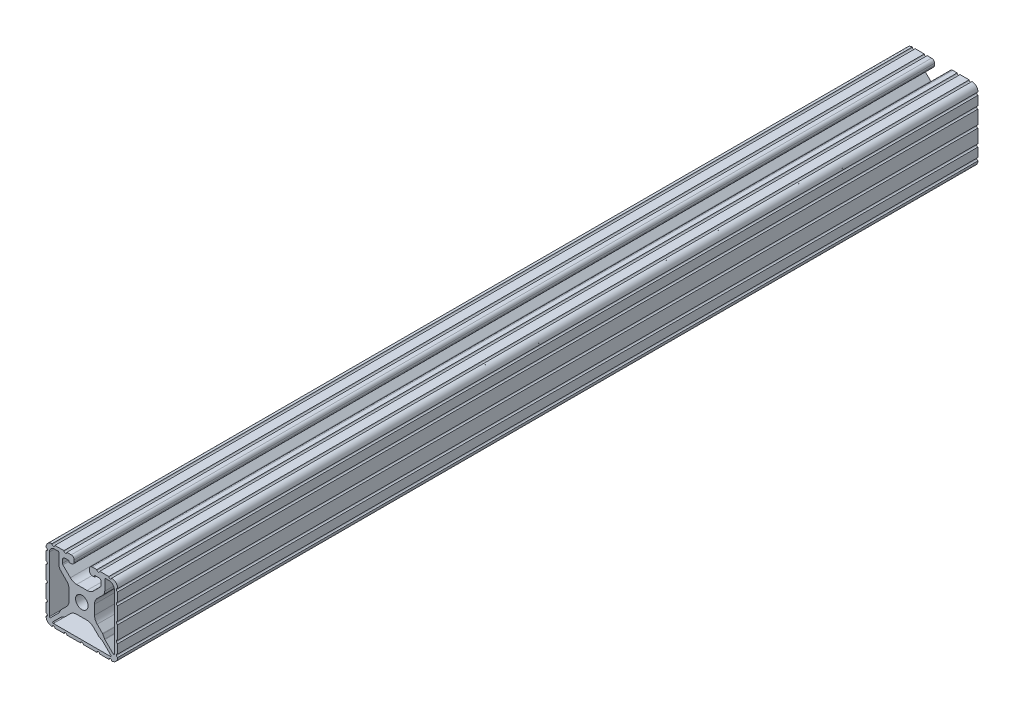
SolidWorks part; units mm, degrees
material "6105-T5 Aluminum"
ref_plane "Front Plane" through (0, 0, 0) normal (0, 0, 1) x (1, 0, 0)
ref_plane "Top Plane" through (0, 0, 0) normal (0, 1, 0) x (1, 0, 0)
ref_plane "Right Plane" through (0, 0, 0) normal (1, 0, 0) x (0, 0, -1)
sketch "Sketch1" plane through (0, 0, 0) normal (0, 0, 1) x (1, 0, 0)
  line L0 (17.272, -15.1936) -> (17.272, 14.478)
  line L1 (12.2663, -11.0145) -> (16.6875, -15.4357)
  line L2 (11.1044, -8.9951) -> (12.14, -10.8475)
  line L3 (8.1475, -5.9974) -> (10.9781, -8.8281)
  line L4 (6.7564, 2.525) -> (6.7564, -2.6388)
  line L5 (11.2435, 8.979) -> (8.1479, 5.8839)
  line L6 (12.1736, 16.891) -> (12.1736, 11.2243)
  line L7 (14.478, 17.272) -> (12.5546, 17.272)
  line L8 (-12.1736, 11.2243) -> (-12.1736, 16.891)
  line L9 (-8.1479, 5.8839) -> (-11.2435, 8.979)
  line L10 (-6.7564, -2.6388) -> (-6.7564, 2.525)
  line L11 (-10.9781, -8.8281) -> (-8.1475, -5.9974)
  line L12 (-12.14, -10.8475) -> (-11.1044, -8.9951)
  line L13 (-16.6875, -15.4357) -> (-12.2663, -11.0145)
  line L14 (-17.272, 14.478) -> (-17.272, -15.1936)
  line L15 (-12.5546, 17.272) -> (-14.478, 17.272)
  line L16 (15.3589, -16.6216) -> (11.091, -12.3537)
  line L17 (-15.0895, -17.272) -> (15.0895, -17.272)
  line L18 (-11.091, -12.3537) -> (-15.3589, -16.6216)
  line L19 (-9.0722, -11.1921) -> (-10.924, -12.2274)
  line L20 (-6.1016, -8.262) -> (-8.9052, -11.0658)
  line L21 (2.7429, -6.8707) -> (-2.7429, -6.8707)
  line L22 (8.9052, -11.0658) -> (6.1016, -8.262)
  line L23 (10.924, -12.2274) -> (9.0722, -11.1921)
  line L24 (6.8141, 15.8247) -> (9.017, 15.8247)
  line L25 (10.287, 14.5547) -> (10.287, 12.8154)
  line L26 (10.0266, 12.1868) -> (6.1008, 8.2616)
  line L27 (2.7424, 6.8707) -> (-2.7424, 6.8707)
  line L28 (-6.1008, 8.2616) -> (-10.0266, 12.1868)
  line L29 (-10.287, 12.8154) -> (-10.287, 14.5547)
  line L30 (-9.017, 15.8247) -> (-6.8141, 15.8247)
  line L31 (-6.8141, 15.8247) -> (-6.8141, 14.986)
  line L32 (-6.8141, 14.986) -> (-5.6388, 14.986)
  line L33 (-4.064, 16.5608) -> (-4.064, 17.4752)
  line L34 (-5.6388, 19.05) -> (-7.9756, 19.05)
  line L35 (-9.4996, 19.05) -> (-14.3256, 19.05)
  line L36 (-15.8496, 19.05) -> (-15.875, 19.05)
  line L37 (-19.05, 15.875) -> (-19.05, 15.8496)
  line L38 (-19.05, 14.3256) -> (-19.05, 9.4996)
  line L39 (-19.05, 7.9756) -> (-19.05, 0.762)
  line L40 (-19.05, -0.762) -> (-19.05, -7.9756)
  line L41 (-19.05, -9.4996) -> (-19.05, -14.3256)
  line L42 (-19.05, -15.8496) -> (-19.05, -15.875)
  line L43 (-15.875, -19.05) -> (-15.8496, -19.05)
  line L44 (-14.3256, -19.05) -> (-9.4996, -19.05)
  line L45 (-7.9756, -19.05) -> (-0.762, -19.05)
  line L46 (0.762, -19.05) -> (7.9756, -19.05)
  line L47 (9.4996, -19.05) -> (14.3256, -19.05)
  line L48 (15.8496, -19.05) -> (15.875, -19.05)
  line L49 (19.05, -15.875) -> (19.05, -15.8496)
  line L50 (19.05, -14.3256) -> (19.05, -9.4996)
  line L51 (19.05, -7.9756) -> (19.05, -0.762)
  line L52 (19.05, 0.762) -> (19.05, 7.9756)
  line L53 (19.05, 9.4996) -> (19.05, 14.3256)
  line L54 (19.05, 15.8496) -> (19.05, 15.875)
  line L55 (15.875, 19.05) -> (15.8496, 19.05)
  line L56 (14.3256, 19.05) -> (9.4996, 19.05)
  line L57 (7.9756, 19.05) -> (5.6388, 19.05)
  line L58 (4.064, 17.4752) -> (4.064, 16.5608)
  line L59 (5.6388, 14.986) -> (6.8141, 14.986)
  line L60 (6.8141, 14.986) -> (6.8141, 15.8247)
  circle A0 centre (0, 0) radius 3.3274
  arc A1 (17.272, 14.478) -> (14.478, 17.272) centre (14.478, 14.478) ccw
  arc A2 (16.6875, -15.4357) -> (17.272, -15.1936) centre (16.9296, -15.1936) ccw
  arc A3 (12.14, -10.8475) -> (12.2663, -11.0145) centre (12.8051, -10.4757) ccw
  arc A4 (11.1044, -8.9951) -> (10.9781, -8.8281) centre (10.4393, -9.3669) ccw
  arc A5 (6.7564, -2.6388) -> (8.1475, -5.9974) centre (11.5062, -2.6388) ccw
  arc A6 (8.1479, 5.8839) -> (6.7564, 2.525) centre (11.5062, 2.525) ccw
  arc A7 (11.2435, 8.979) -> (12.1736, 11.2243) centre (8.9986, 11.2243) ccw
  arc A8 (12.5546, 17.272) -> (12.1736, 16.891) centre (12.5546, 16.891) ccw
  arc A9 (-12.1736, 16.891) -> (-12.5546, 17.272) centre (-12.5546, 16.891) ccw
  arc A10 (-12.1736, 11.2243) -> (-11.2435, 8.979) centre (-8.9986, 11.2243) ccw
  arc A11 (-6.7564, 2.525) -> (-8.1479, 5.8839) centre (-11.5062, 2.525) ccw
  arc A12 (-8.1475, -5.9974) -> (-6.7564, -2.6388) centre (-11.5062, -2.6388) ccw
  arc A13 (-10.9781, -8.8281) -> (-11.1044, -8.9951) centre (-10.4393, -9.3669) ccw
  arc A14 (-12.2663, -11.0145) -> (-12.14, -10.8475) centre (-12.8051, -10.4757) ccw
  arc A15 (-17.272, -15.1936) -> (-16.6875, -15.4357) centre (-16.9296, -15.1936) ccw
  arc A16 (-14.478, 17.272) -> (-17.272, 14.478) centre (-14.478, 14.478) ccw
  arc A17 (11.091, -12.3537) -> (10.924, -12.2274) centre (10.5522, -12.8925) ccw
  arc A18 (15.0895, -17.272) -> (15.3589, -16.6216) centre (15.0895, -16.891) ccw
  arc A19 (-15.3589, -16.6216) -> (-15.0895, -17.272) centre (-15.0895, -16.891) ccw
  arc A20 (-10.924, -12.2274) -> (-11.091, -12.3537) centre (-10.5522, -12.8925) ccw
  arc A21 (-9.0722, -11.1921) -> (-8.9052, -11.0658) centre (-9.4441, -10.527) ccw
  arc A22 (-2.7429, -6.8707) -> (-6.1016, -8.262) centre (-2.7429, -11.6205) ccw
  arc A23 (6.1016, -8.262) -> (2.7429, -6.8707) centre (2.7429, -11.6205) ccw
  arc A24 (8.9052, -11.0658) -> (9.0722, -11.1921) centre (9.4441, -10.527) ccw
  arc A25 (10.287, 14.5547) -> (9.017, 15.8247) centre (9.017, 14.5547) ccw
  arc A26 (10.0266, 12.1868) -> (10.287, 12.8154) centre (9.398, 12.8154) ccw
  arc A27 (2.7424, 6.8707) -> (6.1008, 8.2616) centre (2.7424, 11.6205) ccw
  arc A28 (-6.1008, 8.2616) -> (-2.7424, 6.8707) centre (-2.7424, 11.6205) ccw
  arc A29 (-10.287, 12.8154) -> (-10.0266, 12.1868) centre (-9.398, 12.8154) ccw
  arc A30 (-9.017, 15.8247) -> (-10.287, 14.5547) centre (-9.017, 14.5547) ccw
  arc A31 (-5.6388, 14.986) -> (-4.064, 16.5608) centre (-5.6388, 16.5608) ccw
  arc A32 (-4.064, 17.4752) -> (-5.6388, 19.05) centre (-5.6388, 17.4752) ccw
  arc A33 (-9.4996, 19.05) -> (-7.9756, 19.05) centre (-8.7376, 19.05) ccw
  arc A34 (-15.8496, 19.05) -> (-14.3256, 19.05) centre (-15.0876, 19.05) ccw
  arc A35 (-15.875, 19.05) -> (-19.05, 15.875) centre (-15.875, 15.875) ccw
  arc A36 (-19.05, 14.3256) -> (-19.05, 15.8496) centre (-19.05, 15.0876) ccw
  arc A37 (-19.05, 7.9756) -> (-19.05, 9.4996) centre (-19.05, 8.7376) ccw
  arc A38 (-19.05, -0.762) -> (-19.05, 0.762) centre (-19.05, 0) ccw
  arc A39 (-19.05, -9.4996) -> (-19.05, -7.9756) centre (-19.05, -8.7376) ccw
  arc A40 (-19.05, -15.8496) -> (-19.05, -14.3256) centre (-19.05, -15.0876) ccw
  arc A41 (-19.05, -15.875) -> (-15.875, -19.05) centre (-15.875, -15.875) ccw
  arc A42 (-14.3256, -19.05) -> (-15.8496, -19.05) centre (-15.0876, -19.05) ccw
  arc A43 (-7.9756, -19.05) -> (-9.4996, -19.05) centre (-8.7376, -19.05) ccw
  arc A44 (0.762, -19.05) -> (-0.762, -19.05) centre (0, -19.05) ccw
  arc A45 (9.4996, -19.05) -> (7.9756, -19.05) centre (8.7376, -19.05) ccw
  arc A46 (15.8496, -19.05) -> (14.3256, -19.05) centre (15.0876, -19.05) ccw
  arc A47 (15.875, -19.05) -> (19.05, -15.875) centre (15.875, -15.875) ccw
  arc A48 (19.05, -14.3256) -> (19.05, -15.8496) centre (19.05, -15.0876) ccw
  arc A49 (19.05, -7.9756) -> (19.05, -9.4996) centre (19.05, -8.7376) ccw
  arc A50 (19.05, 0.762) -> (19.05, -0.762) centre (19.05, 0) ccw
  arc A51 (19.05, 9.4996) -> (19.05, 7.9756) centre (19.05, 8.7376) ccw
  arc A52 (19.05, 15.8496) -> (19.05, 14.3256) centre (19.05, 15.0876) ccw
  arc A53 (19.05, 15.875) -> (15.875, 19.05) centre (15.875, 15.875) ccw
  arc A54 (14.3256, 19.05) -> (15.8496, 19.05) centre (15.0876, 19.05) ccw
  arc A55 (7.9756, 19.05) -> (9.4996, 19.05) centre (8.7376, 19.05) ccw
  arc A56 (5.6388, 19.05) -> (4.064, 17.4752) centre (5.6388, 17.4752) ccw
  arc A57 (4.064, 16.5608) -> (5.6388, 14.986) centre (5.6388, 16.5608) ccw
extrude "Extrude1" add sketch "Sketch1" against normal blind 457.2
